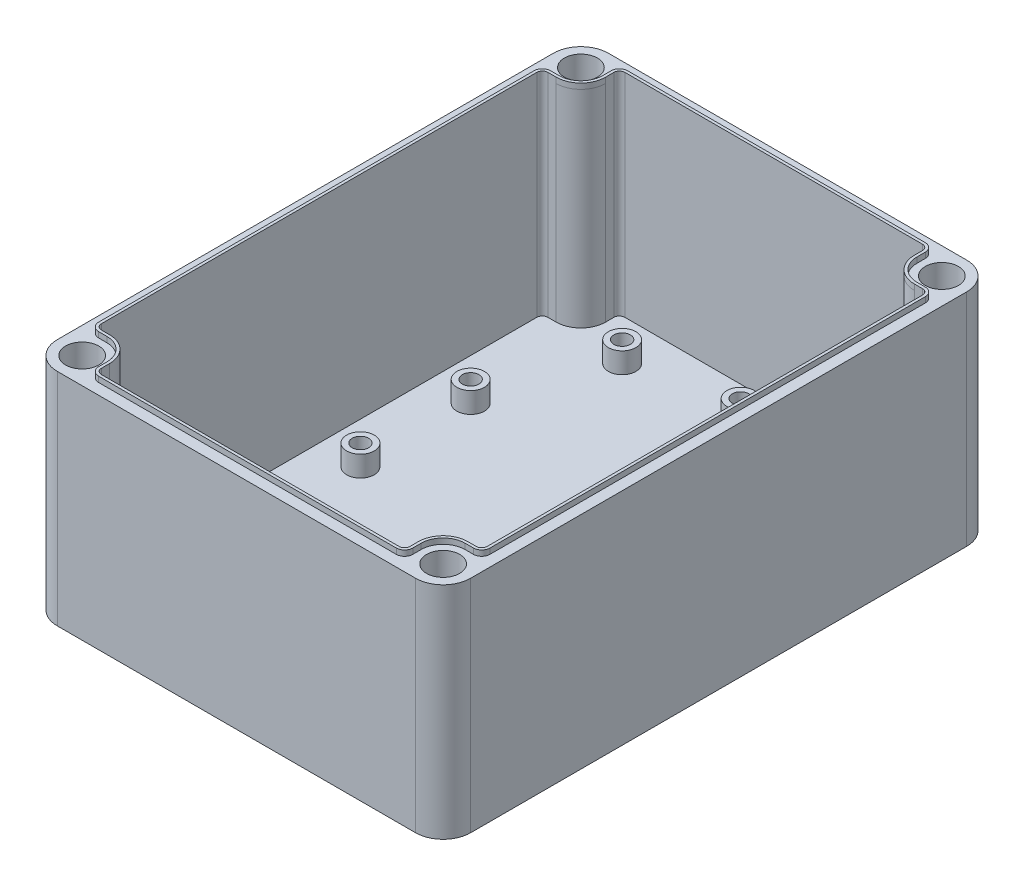
SolidWorks part; units mm, degrees
material "ABS"
ref_plane "Front Plane" through (0, 0, 0) normal (0, 0, 1) x (1, 0, 0)
ref_plane "Top Plane" through (0, 0, 0) normal (0, 1, 0) x (1, 0, 0)
ref_plane "Right Plane" through (0, 0, 0) normal (1, 0, 0) x (0, 0, -1)
sketch "Sketch1" plane through (0, 0, 0) normal (0, 1, 0) x (1, 0, 0)
  line L1 (0, 0) -> (150, 0)
  line L2 (0, 0) -> (0, 200)
  line L3 (0, 200) -> (150, 200)
  line L4 (150, 0) -> (150, 200)
  dimension "D1" = 200
  dimension "D2" = 150
extrude "Boss-Extrude1" add sketch "Sketch1" along normal blind 80
sketch "Sketch2" plane through (0, 80, 0) normal (0, 1, 0) x (1, 0, 0)
  line L0 (150, 200) -> (0, 200) construction
  line L1 (0, 200) -> (0, 0) construction
  line L2 (150, 0) -> (150, 200) construction
  line L3 (0, 0) -> (150, 0) construction
  circle A0 centre (9.5, 190.5) radius 3
  circle A1 centre (140.5, 190.5) radius 3
  circle A2 centre (140.5, 9.5) radius 3
  circle A3 centre (9.5, 9.5) radius 3
  dimension "D1" = 6
  dimension "D6" = 6
  dimension "D7" = 6
  dimension "D8" = 6
  dimension "D2" = 9.5
  dimension "D3" = 9.5
  dimension "D4" = 9.5
  dimension "D5" = 9.5
  dimension "D9" = 9.5
  dimension "D10" = 9.5
  dimension "D11" = 9.5
  dimension "D12" = 9.5
extrude "Hole-1" cut sketch "Sketch2" against normal blind 100
sketch "Sketch3" plane through (0, 80, 0) normal (0, 1, 0) x (1, 0, 0)
  line L0 (21, 194.9731) -> (129, 194.9731)
  line L1 (150, 200) -> (0, 200) construction
  line L2 (5, 179) -> (5, 21)
  line L3 (21, 5) -> (129, 5)
  line L4 (145, 179) -> (145, 21)
  line L5 (0, 200) -> (0, 0) construction
  line L8 (19, 7) -> (19, 10)
  line L9 (7, 19) -> (10, 19)
  line L10 (75, 5) -> (75, 19) construction
  line L11 (143, 19) -> (140, 19)
  line L12 (131, 7) -> (131, 10)
  line L13 (7, 181) -> (10, 181)
  line L14 (19, 192.9731) -> (19, 189.9731)
  line L15 (75, 195) -> (75, 186.0927) construction
  line L16 (131, 192.9731) -> (131, 189.9731)
  line L17 (143, 181) -> (140, 181)
  arc A0 (10, 181) -> (19, 189.9731) centre (10, 190) ccw
  arc A1 (19, 192.9731) -> (21, 194.9731) centre (21, 192.9731) cw
  arc A2 (10, 19) -> (19, 10) centre (10, 10) cw
  arc A3 (7, 181) -> (5, 179) centre (7, 179) ccw
  arc A4 (140, 19) -> (131, 10) centre (140, 10) ccw
  arc A5 (143, 181) -> (145, 179) centre (143, 179) cw
  arc A6 (131, 192.9731) -> (129, 194.9731) centre (129, 192.9731) ccw
  arc A7 (140, 181) -> (131, 189.9731) centre (140, 190) cw
  arc A8 (143, 19) -> (145, 21) centre (143, 21) ccw
  arc A9 (7, 19) -> (5, 21) centre (7, 21) cw
  arc A10 (19, 7) -> (21, 5) centre (21, 7) ccw
  arc A11 (131, 7) -> (129, 5) centre (129, 7) cw
  point P1 (145, 5)
  point P2 (5, 5)
  point P15 (145, 19)
  point P34 (19, 194.9731)
  point P37 (5, 181)
  point P48 (5, 19)
  point P51 (19, 5)
  point P54 (131, 5)
  dimension "D11" = 2
  dimension "D4" = 2
  dimension "D3" = 2
  dimension "D2" = 5
  dimension "D5" = 19
  dimension "D6" = 19
  dimension "D7" = 5
  dimension "D8" = 5
extrude "Cut-Extrude2" cut sketch "Sketch3" against normal blind 75
fillet "Fillet1" radius 10 4 edges at (0, 40, -200) (150, 40, -200) (0, 40, 0) (150, 40, 0)
sketch "Sketch4" plane through (0, 80, 0) normal (0, 1, 0) x (1, 0, 0)
  line L0 (5, 179) -> (5, 21)
  line L1 (4, 179) -> (4, 21)
  line L2 (7, 19) -> (10, 19)
  line L3 (7, 18) -> (10, 18)
  line L4 (19, 10) -> (19, 7)
  line L5 (18, 10) -> (18, 7)
  line L6 (21, 5) -> (129, 5)
  line L7 (21, 4) -> (129, 4)
  line L8 (131, 7) -> (131, 10)
  line L9 (132, 7) -> (132, 10)
  line L10 (140, 19) -> (143, 19)
  line L11 (140, 18) -> (143, 18)
  line L12 (145, 21) -> (145, 179)
  line L13 (146, 21) -> (146, 179)
  line L14 (143, 181) -> (140, 181)
  line L15 (143, 182) -> (139.9985, 182)
  line L16 (131, 189.9731) -> (131, 192.9731)
  line L17 (132, 189.9731) -> (132, 192.9731)
  line L18 (129, 194.9731) -> (21, 194.9731)
  line L19 (129, 195.9731) -> (21, 195.9731)
  line L20 (19, 192.9731) -> (19, 189.9731)
  line L21 (18, 192.9731) -> (18, 189.9731)
  line L22 (10, 181) -> (7, 181)
  line L23 (10.0015, 182) -> (7, 182)
  arc A0 (5, 179) -> (7, 181) centre (7, 179) cw
  arc A1 (19, 192.9731) -> (21, 194.9731) centre (21, 192.9731) cw
  arc A2 (19, 189.9731) -> (10, 181) centre (10.0268, 189.9731) cw
  arc A3 (129, 194.9731) -> (131, 192.9731) centre (129, 192.9731) cw
  arc A4 (143, 181) -> (145, 179) centre (143, 179) cw
  arc A5 (131, 189.9731) -> (140, 181) centre (139.9732, 189.9731) ccw
  arc A6 (143, 19) -> (145, 21) centre (143, 21) ccw
  arc A7 (140, 19) -> (131, 10) centre (140, 10) ccw
  arc A8 (129, 5) -> (131, 7) centre (129, 7) ccw
  arc A9 (5, 21) -> (7, 19) centre (7, 21) ccw
  arc A10 (10, 19) -> (19, 10) centre (10, 10) cw
  arc A11 (21, 5) -> (19, 7) centre (21, 7) cw
  arc A12 (4, 21) -> (7, 18) centre (7, 21) ccw
  arc A13 (10, 18) -> (18, 10) centre (10, 10) cw
  arc A14 (21, 4) -> (18, 7) centre (21, 7) cw
  arc A15 (129, 4) -> (132, 7) centre (129, 7) ccw
  arc A16 (140, 18) -> (132, 10) centre (140, 10) ccw
  arc A17 (143, 18) -> (146, 21) centre (143, 21) ccw
  arc A18 (143, 182) -> (146, 179) centre (143, 179) cw
  arc A19 (132, 189.9731) -> (139.9985, 182) centre (139.9732, 189.9731) ccw
  arc A20 (129, 195.9731) -> (132, 192.9731) centre (129, 192.9731) cw
  arc A21 (18, 192.9731) -> (21, 195.9731) centre (21, 192.9731) cw
  arc A22 (18, 189.9731) -> (10.0015, 182) centre (10.0268, 189.9731) cw
  arc A23 (4, 179) -> (7, 182) centre (7, 179) cw
  dimension "D1" = 1
extrude "Boss-Extrude2" add sketch "Sketch4" along normal blind 2
sketch "Sketch5" plane through (0, 80, 0) normal (0, 1, 0) x (1, 0, 0)
  circle A1 centre (9.5, 9.5) radius 6
  circle A2 centre (140.5, 9.5) radius 6
  circle A3 centre (140.5, 190.5) radius 6
  circle A4 centre (9.5, 190.5) radius 6
extrude "Hole-2" cut sketch "Sketch5" against normal blind 90
sketch "Sketch6" plane through (0, 5, 0) normal (0, 1, 0) x (1, 0, 0)
  line L0 (75, 194.9731) -> (75, 5) construction
  line L1 (129, 194.9731) -> (21, 194.9731) construction
  line L2 (21, 5) -> (129, 5) construction
  line L3 (129, 194.9731) -> (21, 194.9731) construction
  line L4 (145, 21) -> (145, 179) construction
  line L5 (145, 100) -> (5, 100) construction
  line L6 (5, 179) -> (5, 21) construction
  circle A0 centre (130, 100) radius 5
  circle A1 centre (130, 100) radius 3
  circle A2 centre (130, 140) radius 5
  circle A3 centre (130, 140) radius 3
  circle A4 centre (115, 179.9731) radius 5
  circle A5 centre (115, 179.9731) radius 3
  circle A6 centre (35, 179.9731) radius 3
  circle A7 centre (35, 179.9731) radius 5
  circle A8 centre (20, 140) radius 3
  circle A9 centre (20, 140) radius 5
  circle A10 centre (20, 100) radius 3
  circle A11 centre (20, 100) radius 5
  circle A12 centre (75, 182.9731) radius 5
  circle A13 centre (75, 182.9731) radius 3
  circle A14 centre (75, 17.0269) radius 3
  circle A15 centre (75, 17.0269) radius 5
  circle A16 centre (20, 60) radius 5
  circle A17 centre (20, 60) radius 3
  circle A18 centre (35, 20.0269) radius 5
  circle A19 centre (35, 20.0269) radius 3
  circle A20 centre (115, 20.0269) radius 3
  circle A21 centre (115, 20.0269) radius 5
  circle A22 centre (130, 60) radius 3
  circle A23 centre (130, 60) radius 5
  dimension "D1" = 55
  dimension "D4" = 15
  dimension "D5" = 30
  dimension "D7" = 12
  dimension "D2" = 2
  dimension "D6" = 2
  dimension "D3" = 2
extrude "Boss-Extrude3" add sketch "Sketch6" along normal blind 7.5
